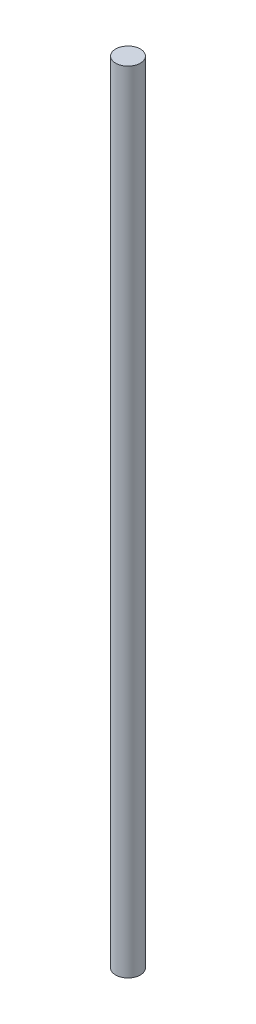
SolidWorks part; units mm, degrees
ref_plane "Front Plane" through (0, 0, 0) normal (0, 0, 1) x (1, 0, 0)
ref_plane "Top Plane" through (0, 0, 0) normal (0, 1, 0) x (1, 0, 0)
ref_plane "Right Plane" through (0, 0, 0) normal (1, 0, 0) x (0, 0, -1)
sketch "Sketch1" plane through (0, 0, 0) normal (0, 1, 0) x (1, 0, 0)
  circle A0 centre (0, 0) radius 6.35
  dimension "D1" = 12.7
extrude "Boss-Extrude1" add sketch "Sketch1" along normal blind 406.4
